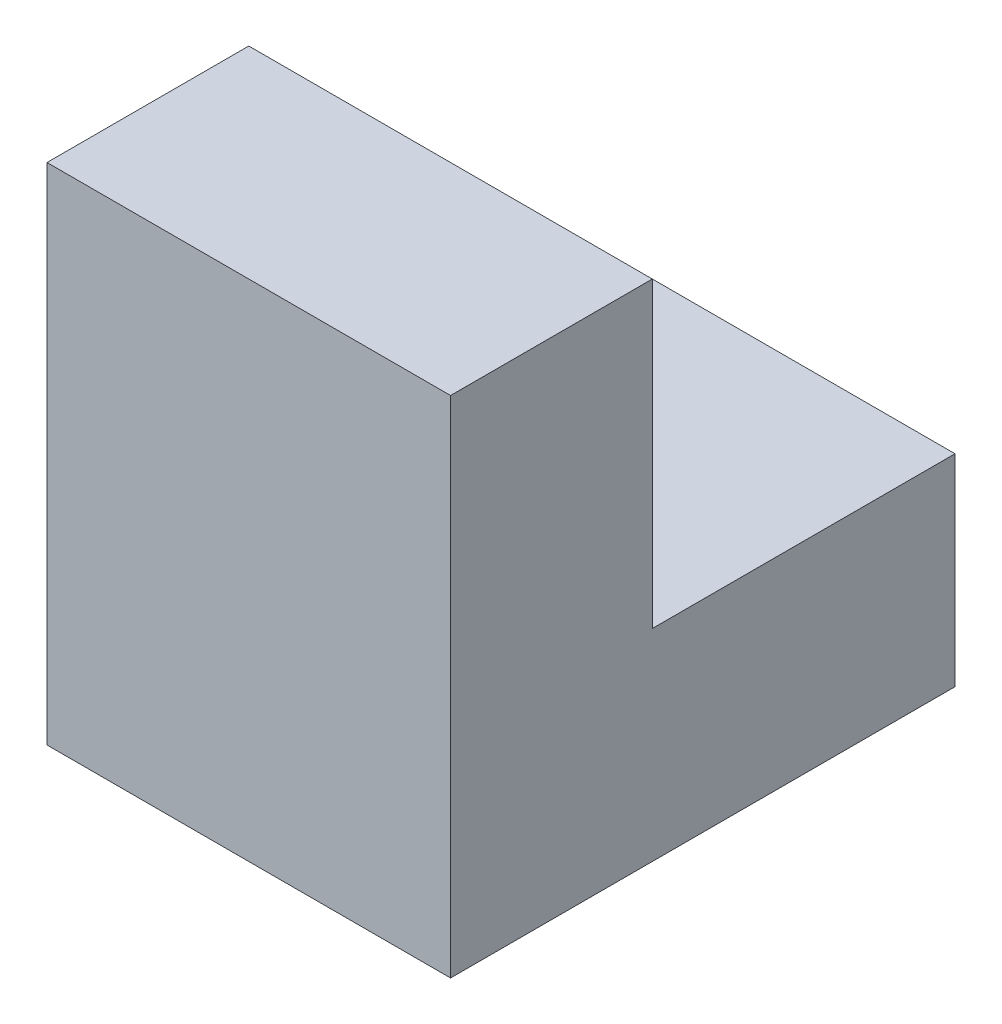
SolidWorks part; units mm, degrees
ref_plane "Front Plane" through (0, 0, 0) normal (0, 0, 1) x (1, 0, 0)
ref_plane "Top Plane" through (0, 0, 0) normal (0, 1, 0) x (1, 0, 0)
ref_plane "Right Plane" through (0, 0, 0) normal (1, 0, 0) x (0, 0, -1)
sketch "Sketch2" plane through (0, 0, 0) normal (1, 0, 0) x (0, 0, -1)
  line L0 (0, 50) -> (0, 0)
  line L3 (0, 50) -> (20, 50)
  line L4 (20, 20) -> (20, 50)
  line L7 (20, 20) -> (50, 20)
  line L8 (50, 0) -> (50, 20)
  line L9 (0, 0) -> (50, 0)
  dimension "D1" = 20
  dimension "D2" = 20
  dimension "D3" = 30
  dimension "D4" = 30
extrude "Boss-Extrude1" add sketch "Sketch2" along normal blind 40
